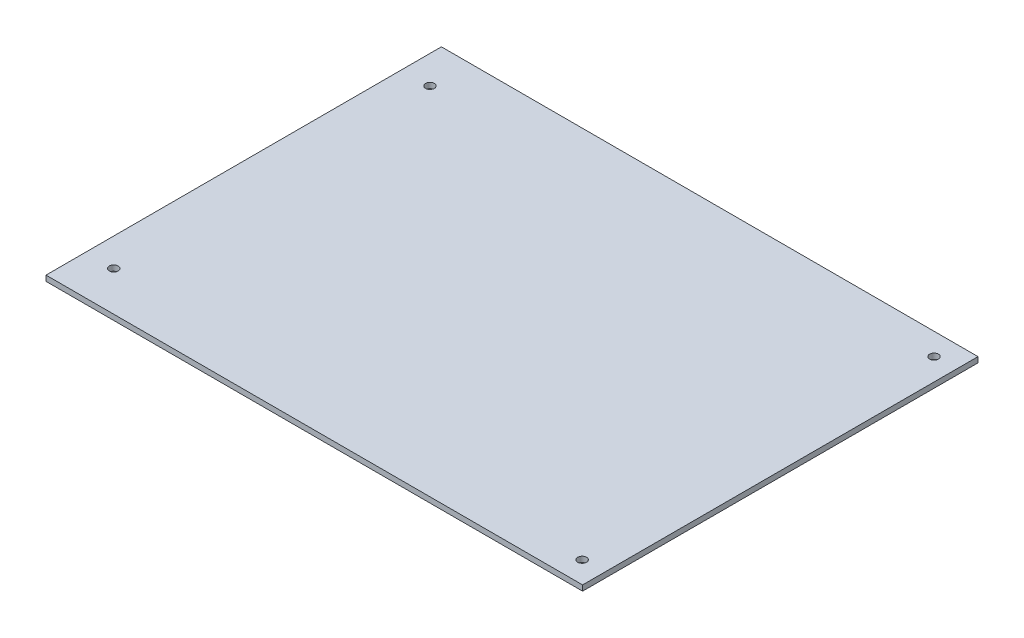
SolidWorks part; units mm, degrees
ref_plane "Front Plane" through (0, 0, 0) normal (0, 0, 1) x (1, 0, 0)
ref_plane "Top Plane" through (0, 0, 0) normal (0, 1, 0) x (1, 0, 0)
ref_plane "Right Plane" through (0, 0, 0) normal (1, 0, 0) x (0, 0, -1)
sketch "Sketch1" plane through (0, 0, 0) normal (0, 1, 0) x (1, 0, 0)
  line L1 (-77.47, 57.0865) -> (77.47, 57.0865)
  line L2 (-77.47, 57.0865) -> (-77.47, -57.0865)
  line L3 (-77.47, -57.0865) -> (77.47, -57.0865)
  line L4 (77.47, 57.0865) -> (77.47, -57.0865)
  line L5 (-77.47, 57.0865) -> (77.47, -57.0865) construction
  line L6 (-77.47, -57.0865) -> (77.47, 57.0865) construction
  circle A0 centre (71.12, -50.8635) radius 1.27
  circle A1 centre (71.12, 50.7365) radius 1.27
  circle A2 centre (-69.342, 45.6565) radius 1.27
  circle A3 centre (-69.342, -45.6565) radius 1.27
  point P0 (0, 0)
  point P14 (0, 0)
  point P15 (0, 0)
  dimension "D6" = 2.54
  dimension "D9" = 2.54
  dimension "D1" = 154.94
  dimension "D2" = 114.173
  dimension "D3" = 101.6
  dimension "D4" = 6.35
  dimension "D5" = 6.35
  dimension "D7" = 11.43
  dimension "D8" = 8.128
  dimension "D10" = 11.43
extrude "Boss-Extrude1" add sketch "Sketch1" along normal blind 1.5748
